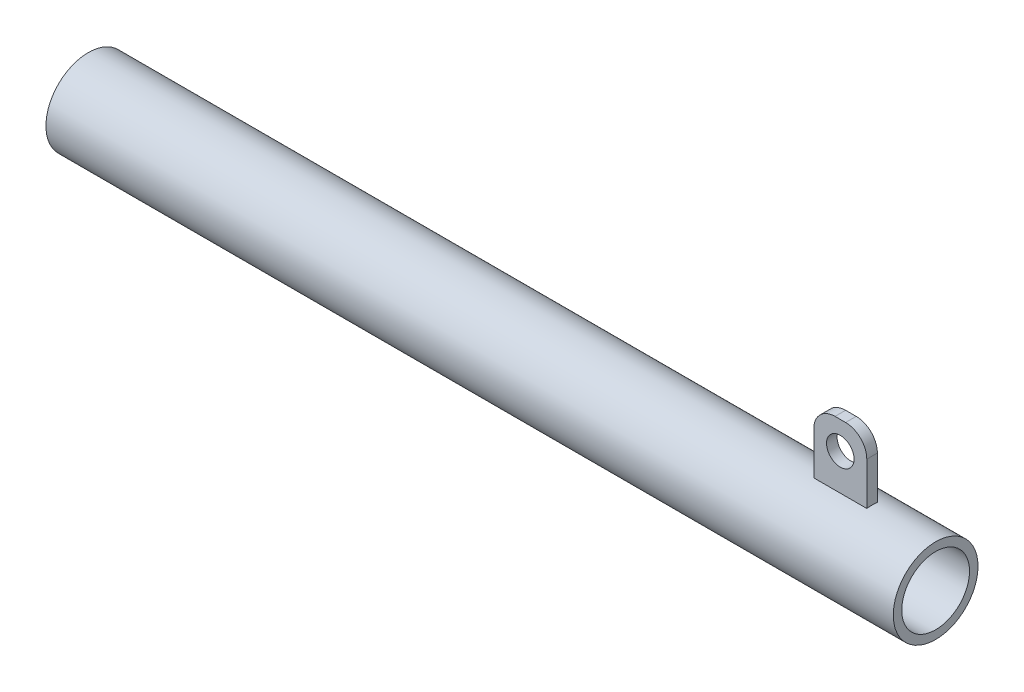
SolidWorks part; units mm, degrees
ref_plane "Front Plane" through (0, 0, 0) normal (0, 0, 1) x (1, 0, 0)
ref_plane "Top Plane" through (0, 0, 0) normal (0, 1, 0) x (1, 0, 0)
ref_plane "Right Plane" through (0, 0, 0) normal (1, 0, 0) x (0, 0, -1)
sketch "Sketch1" plane through (0, 0, 0) normal (1, 0, 0) x (0, 0, -1)
  circle A0 centre (0, 0) radius 20
  circle A1 centre (0, 0) radius 16
  dimension "D1" = 40
  dimension "D2" = 32
extrude "Boss-Extrude1" add sketch "Sketch1" against normal blind 400
ref_plane "Plane1" through (0, 50, 0) normal (0, 1, 0) x (1, 0, 0)
sketch "Sketch2" plane through (0, 50, 0) normal (0, 1, 0) x (1, 0, 0)
  line L0 (0, 0) -> (-473.2116, 0) construction
  line L1 (0, -20) -> (0, 20) construction
  line L2 (-55, 2.5) -> (-30, 2.5)
  line L3 (-55, 2.5) -> (-55, -2.5)
  line L4 (-55, -2.5) -> (-30, -2.5)
  line L5 (-30, 2.5) -> (-30, -2.5)
  line L6 (-55, 2.5) -> (-30, -2.5) construction
  line L7 (-55, -2.5) -> (-30, 2.5) construction
  point P3 (-42.5, 0)
  dimension "D1" = 25
  dimension "D2" = 5
  dimension "D3" = 30
extrude "Boss-Extrude2" add sketch "Sketch2" against normal up to surface (30.1569 mm away)
fillet "Fillet1" radius 10 2 edges at (-30, 50, 0) (-55, 50, 0)
sketch "Sketch3" plane through (0, 0, 2.5) normal (0, 0, 1) x (1, 0, 0)
  line L0 (-42.5, 50) -> (-42.5, 19.8431) construction
  line L1 (-45, 50) -> (-40, 50) construction
  line L2 (-30, 19.8431) -> (-55, 19.8431) construction
  circle A0 centre (-42.5, 37) radius 6.5
  dimension "D1" = 13
  dimension "D2" = 13
extrude "Cut-Extrude1" cut sketch "Sketch3" against normal blind 10
